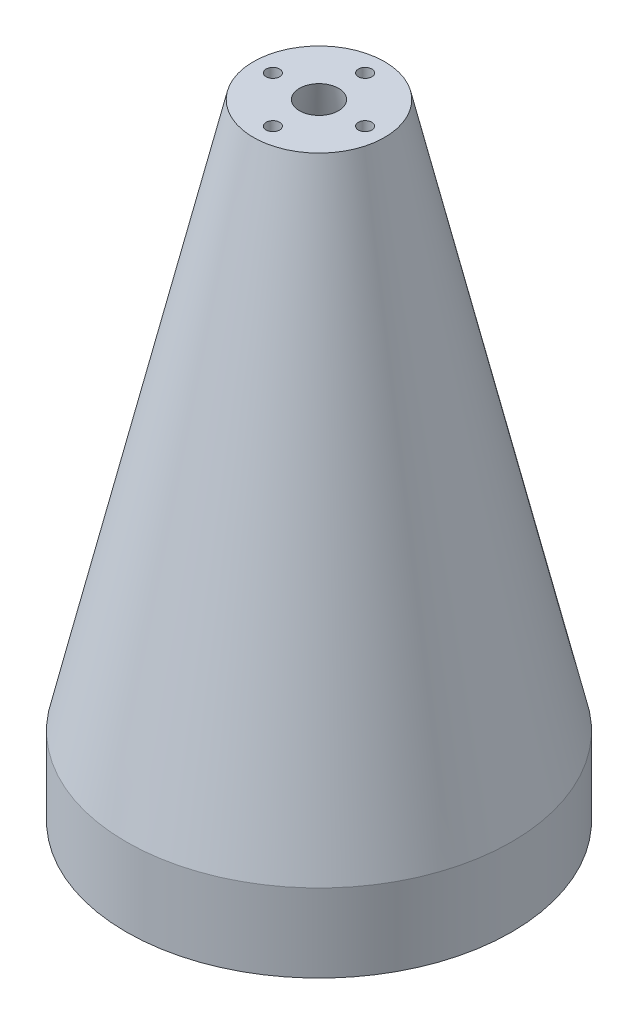
SolidWorks part; units mm, degrees
ref_plane "Front Plane" through (0, 0, 0) normal (0, 0, 1) x (1, 0, 0)
ref_plane "Top Plane" through (0, 0, 0) normal (0, 1, 0) x (1, 0, 0)
ref_plane "Right Plane" through (0, 0, 0) normal (1, 0, 0) x (0, 0, -1)
sketch "Sketch2" plane through (0, 0, 0) normal (0, 0, 1) x (1, 0, 0)
  line L0 (50.8635, 0) -> (62.6885, 0)
  line L1 (62.6885, 0) -> (62.6885, 25.4)
  line L2 (62.6885, 25.4) -> (21.35, 203.2)
  line L3 (21.35, 203.2) -> (6.35, 203.2)
  line L4 (6.35, 203.2) -> (47.6885, 25.4)
  line L5 (47.6885, 25.4) -> (47.6885, 4.064)
  line L6 (0, 0) -> (0, 132.4998) construction
  line L10 (47.6885, 4.064) -> (50.8635, 4.064)
  line L11 (50.8635, 0) -> (50.8635, 4.064)
  point P3 (13.85, 203.2)
  dimension "D1" = 101.727
  dimension "D2" = 15
  dimension "D3" = 203.2
  dimension "D4" = 12.7
  dimension "D5" = 25.4
  dimension "D6" = 3.175
  dimension "D7" = 4.064
  dimension "D8" = 15
  dimension "D9" = 125.377
revolve "Revolve1" add sketch "Sketch2" angle 360 about L6
sketch "Sketch3" plane through (0, 0, 0) normal (0, -1, 0) x (1, 0, 0)
  line L0 (-69.9213, 0) -> (69.9213, 0) construction
  line L1 (0, -68.1104) -> (0, 67.4546) construction
  circle A0 centre (-57.9825, 0) radius 2.2
  circle A1 centre (0, 57.9825) radius 2.2
  circle A2 centre (57.9825, 0) radius 2.2
  circle A3 centre (0, -57.9825) radius 2.2
  circle A4 centre (0, 0) radius 57.9825 construction
  circle A5 centre (0, 0) radius 50.8635 construction
  circle A6 centre (0, 0) radius 62.6885 construction
  dimension "D1" = 115.965
  dimension "D2" = 7.119
  dimension "D3" = 4.706
  dimension "D4" = 4.4
extrude "Cut-Extrude1" cut sketch "Sketch3" against normal blind 10
sketch "Sketch4" plane through (0, 203.2, 0) normal (0, 1, 0) x (1, 0, 0)
  circle A0 centre (0, 0) radius 15 construction
  circle A1 centre (-15, 0) radius 2.2
  circle A2 centre (0, 15) radius 2.2
  circle A3 centre (15, 0) radius 2.2
  circle A4 centre (0, -15) radius 2.2
  dimension "D1" = 30
  dimension "D2" = 4.4
extrude "Cut-Extrude2" cut sketch "Sketch4" against normal blind 10
